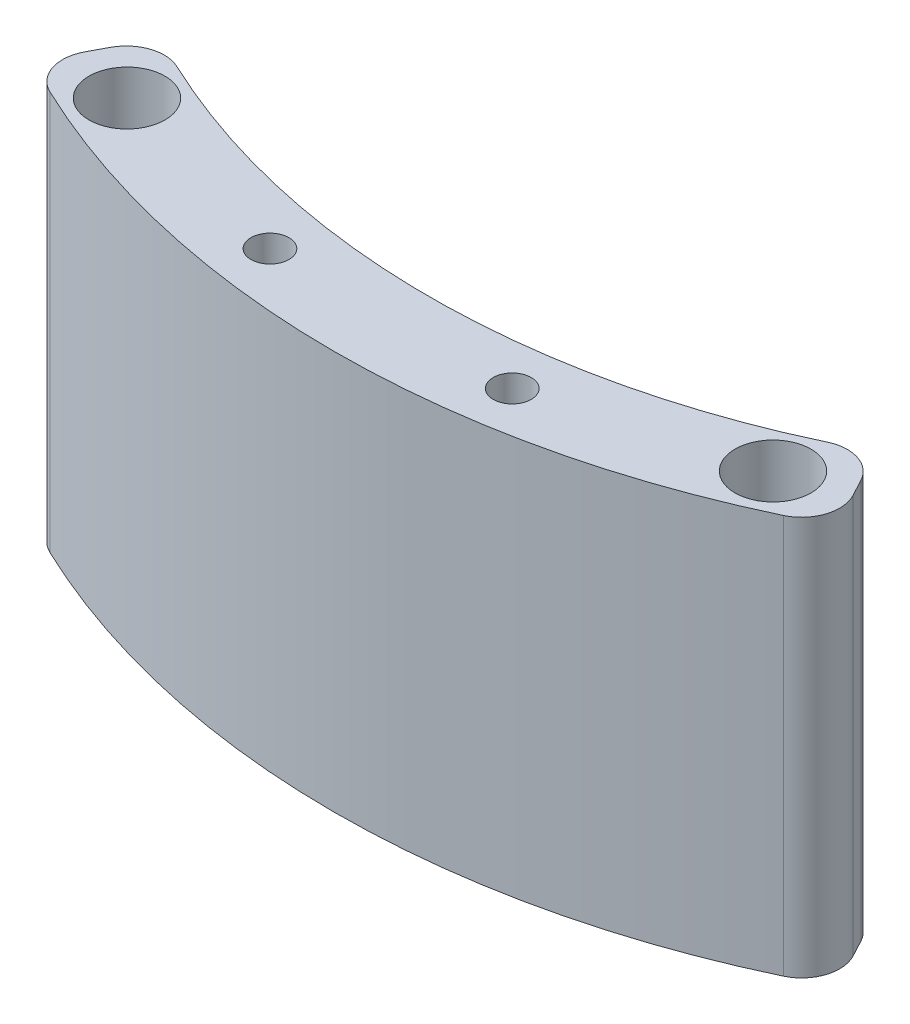
SolidWorks part; units mm, degrees
ref_plane "Front Plane" through (0, 0, 0) normal (0, 0, 1) x (1, 0, 0)
ref_plane "Top Plane" through (0, 0, 0) normal (0, 1, 0) x (1, 0, 0)
ref_plane "Right Plane" through (0, 0, 0) normal (1, 0, 0) x (0, 0, -1)
sketch "Sketch1" plane through (0, 0, 0) normal (0, 1, 0) x (1, 0, 0)
  line L0 (-40, 15) -> (40, 15) construction
  line L1 (-37.6471, 19.4118) -> (-42.3529, 10.5882)
  line L2 (37.6471, 19.4118) -> (42.3529, 10.5882)
  arc A0 (-42.3529, 10.5882) -> (42.3529, 10.5882) centre (0, 90) ccw
  arc A1 (-37.6471, 19.4118) -> (37.6471, 19.4118) centre (0, 90) ccw
  arc A2 (-40, 15) -> (40, 15) centre (0, 90) ccw construction
  point P7 (0, 0)
  point P10 (0, 0)
  dimension "D1" = 180
  dimension "D2" = 160
  dimension "D3" = 170
  dimension "D4" = 80
extrude "Boss-Extrude1" add sketch "Sketch1" along normal blind 42
fillet "Fillet1" radius 4 4 edges at (-37.6471, 21, -19.4118) (-42.3529, 21, -10.5882) (37.6471, 21, -19.4118) (42.3529, 21, -10.5882)
sketch "Sketch2" plane through (0, 42, 0) normal (0, 1, 0) x (1, 0, 0)
  line L0 (-34, 12.2) -> (34, 12.2) construction
  line L1 (0, 12.2) -> (0, 0) construction
  circle A0 centre (-34, 12.2) radius 4
  circle A1 centre (34, 12.2) radius 4
  point P7 (0, 12.7)
  dimension "D3" = 8
  dimension "D4" = 8
  dimension "D1" = 68
  dimension "D2" = 12.2
extrude "Cut-Extrude1" cut sketch "Sketch2" against normal blind 42
sketch "Sketch3" plane through (0, 42, 0) normal (0, 1, 0) x (1, 0, 0)
  line L0 (-12.75, 6) -> (12.75, 6) construction
  line L1 (0, 6) -> (0, 0) construction
  circle A0 centre (-12.75, 6) radius 2
  circle A1 centre (12.75, 6) radius 2
  dimension "D3" = 4
  dimension "D4" = 4
  dimension "D1" = 25.5
  dimension "D2" = 6
extrude "Cut-Extrude2" cut sketch "Sketch3" against normal blind 42
